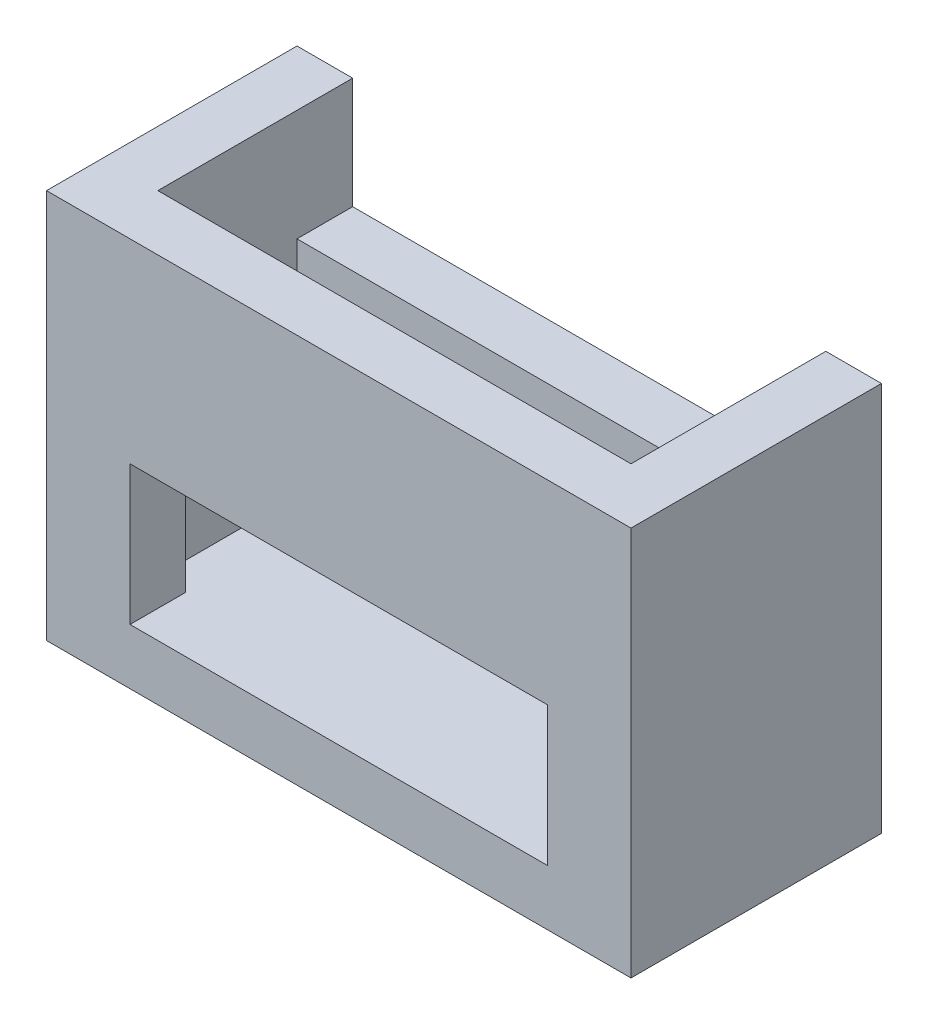
SolidWorks part; units mm, degrees
ref_plane "Front Plane" through (0, 0, 0) normal (0, 0, 1) x (1, 0, 0)
ref_plane "Top Plane" through (0, 0, 0) normal (0, 1, 0) x (1, 0, 0)
ref_plane "Right Plane" through (0, 0, 0) normal (1, 0, 0) x (0, 0, -1)
sketch "Sketch2" plane through (0, 0, 0) normal (0, 0, 1) x (1, 0, 0)
  line L1 (-10.5, 7) -> (10.5, 7)
  line L2 (-10.5, 7) -> (-10.5, -7)
  line L3 (-10.5, -7) -> (10.5, -7)
  line L4 (10.5, 7) -> (10.5, -7)
  line L5 (-10.5, 7) -> (10.5, -7) construction
  line L6 (-10.5, -7) -> (10.5, 7) construction
  point P0 (0, 0)
  dimension "D1" = 21
  dimension "D2" = 14
extrude "Boss-Extrude1" add sketch "Sketch2" along normal blind 9
sketch "Sketch3" plane through (0, 0, 9) normal (0, 0, 1) x (1, 0, 0)
  line L0 (-10.5, -7) -> (-8.5, -7)
  line L1 (-10.5, -7) -> (10.5, -7) construction
  line L2 (-10.5, -7) -> (-10.5, -5)
  line L3 (-10.5, 7) -> (-10.5, -7) construction
  line L4 (-10.5, -5) -> (-10.5, 0)
  line L6 (-7.5, -5) -> (7.5, -5)
  line L7 (-7.5, -5) -> (-7.5, 0)
  line L8 (-7.5, 0) -> (7.5, 0)
  line L9 (7.5, -5) -> (7.5, 0)
  dimension "D1" = 2
  dimension "D2" = 2
  dimension "D3" = 5
  dimension "D4" = 15
extrude "Cut-Extrude1" cut sketch "Sketch3" against normal blind 5 contours L6 L9 L8 L7
sketch "Sketch6" plane through (0, 7, 0) normal (0, 1, 0) x (1, 0, 0)
  line L0 (-10.5, -9) -> (-10.5, -7)
  line L1 (-10.5, -9) -> (-10.5, 0) construction
  line L2 (-10.5, -9) -> (-8.5, -9)
  line L3 (10.5, -9) -> (-10.5, -9) construction
  line L4 (10.5, 0) -> (8.5, 0)
  line L5 (10.5, 0) -> (-10.5, 0) construction
  line L6 (10.5, 0) -> (10.5, -2)
  line L7 (10.5, -9) -> (10.5, 0) construction
  line L9 (-8.5, -7) -> (8.5, -7)
  line L10 (-8.5, -7) -> (-8.5, 0)
  line L11 (-8.5, 0) -> (8.5, 0)
  line L12 (8.5, -7) -> (8.5, 0)
  line M5 (10.5, 0) -> (-10.5, 0)
  dimension "D1" = 2
  dimension "D2" = 2
  dimension "D3" = 2
  dimension "D4" = 2
  dimension "D5" = 17
extrude "Cut-Extrude3" cut sketch "Sketch6" against normal blind 4 contours L9 L12 L10 M5
sketch "Sketch7" plane through (0, 3, 0) normal (0, 1, 0) x (1, 0, 0)
  line L0 (8.5, 0) -> (8.5, -2)
  line L1 (8.5, -7) -> (8.5, 0) construction
  line L2 (-8.5, -7) -> (-8.5, 0) construction
  line L3 (8.5, -2) -> (-8.5, -2)
  line L4 (8.5, -2) -> (8.5, -7)
  line L5 (8.5, -7) -> (-8.5, -7)
  line L6 (-8.5, -2) -> (-8.5, -7)
  line L7 (-8.5, -7) -> (8.5, -7) construction
  line M2 (-8.5, -7) -> (8.5, -7)
  line M3 (8.5, -7) -> (8.5, 0)
  line M5 (-8.5, 0) -> (-8.5, -7)
  dimension "D1" = 2
extrude "Cut-Extrude4" cut sketch "Sketch7" against normal blind 4 contours L3 M3 M5 M2
sketch "Sketch8" plane through (0, -1, 0) normal (0, 1, 0) x (1, 0, 0)
  line L1 (-8.5, -7) -> (-7.5, -7)
  line L2 (-8.5, -7) -> (-8.5, -4)
  line L3 (-8.5, -4) -> (-7.5, -4)
  line L4 (-7.5, -7) -> (-7.5, -4)
  line L5 (8.5, -7) -> (7.5, -7)
  line L6 (8.5, -7) -> (8.5, -4)
  line L7 (8.5, -4) -> (7.5, -4)
  line L8 (7.5, -7) -> (7.5, -4)
extrude "Cut-Extrude6" cut sketch "Sketch8" against normal blind 4 contours L2 L1 L4 L3 | L6 L5 L8 L7
